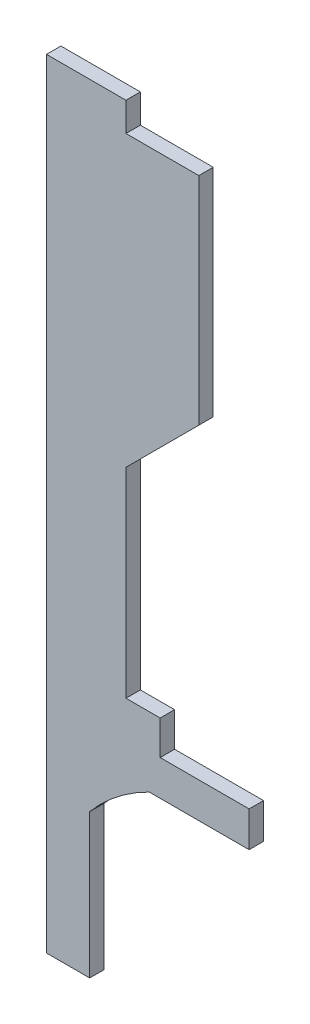
SolidWorks part; units mm, degrees
material "Balsa"
ref_plane "Plan de face" through (0, 0, 0) normal (0, 0, 1) x (1, 0, 0)
ref_plane "Plan de dessus" through (0, 0, 0) normal (0, 1, 0) x (1, 0, 0)
ref_plane "Plan de droite" through (0, 0, 0) normal (1, 0, 0) x (0, 0, -1)
sketch "Esquisse1" plane through (0, 0, 0) normal (0, 0, 1) x (1, 0, 0)
  line L0 (70.2972, 66.1864) -> (70.2972, 78.4512)
  line L1 (0, 270) -> (27.5725, 270)
  line L2 (70.2972, 78.4512) -> (39.4393, 78.4512)
  line L3 (15, 50) -> (15, 0)
  line L4 (0, 270) -> (0, 0)
  line L5 (15, 0) -> (0, 0)
  line L6 (27.5725, 270) -> (27.5725, 260)
  line L7 (35.67, 66.1864) -> (70.2972, 66.1864)
  line L8 (27.5725, 159.7175) -> (52.855, 185)
  line L9 (52.855, 185) -> (52.855, 260)
  line L10 (27.5725, 260) -> (52.855, 260)
  line L11 (27.5725, 159.7175) -> (27.5725, 90.334)
  line L12 (27.5725, 90.334) -> (39.4393, 90.334)
  line L13 (39.4393, 90.334) -> (39.4393, 78.4512)
  arc A0 (15, 50) -> (35.67, 66.1864) centre (63.603, 9.2251) cw
  dimension "D1" = 270
  dimension "D2" = 10
  dimension "D3" = 15
  dimension "D4" = 50
  dimension "D5" = 75
  dimension "D6" = 135
extrude "Boss.-Extru.1" add sketch "Esquisse1" along normal blind 5
